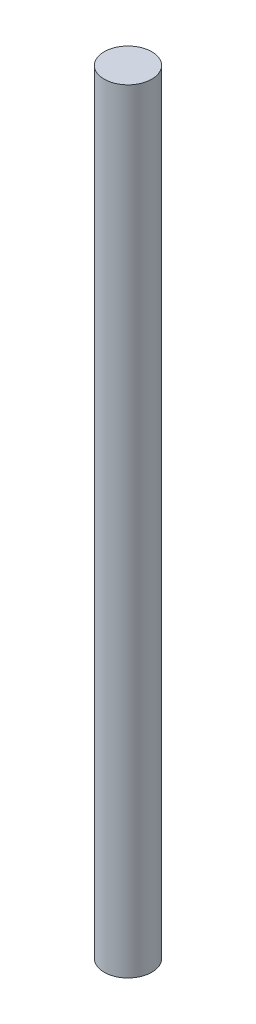
SolidWorks part; units mm, degrees
ref_plane "Plano frontal" through (0, 0, 0) normal (0, 0, 1) x (1, 0, 0)
ref_plane "Plano superior" through (0, 0, 0) normal (0, 1, 0) x (1, 0, 0)
ref_plane "Plano direito" through (0, 0, 0) normal (1, 0, 0) x (0, 0, -1)
sketch "Esboço1" plane through (0, 0, 0) normal (0, 1, 0) x (1, 0, 0)
  circle A0 centre (0, 0) radius 10
  dimension "D1" = 20
extrude "Ressalto-extrusão1" add sketch "Esboço1" along normal blind 325
